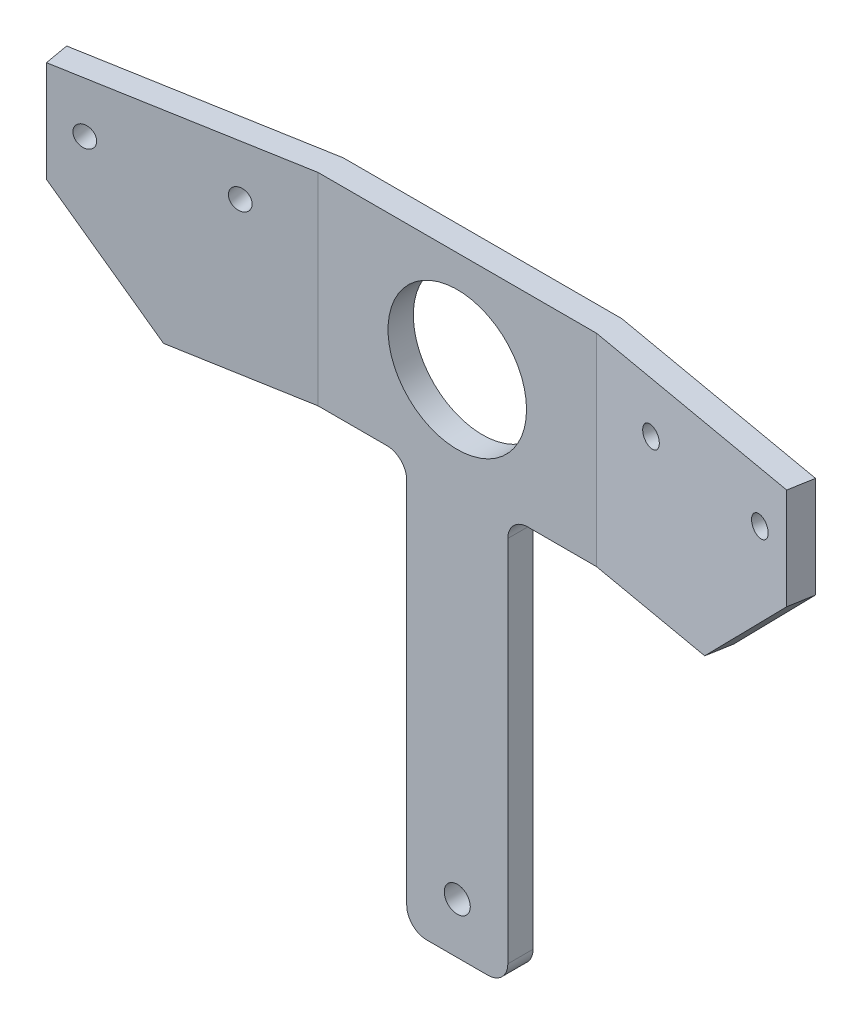
SolidWorks part; units mm, degrees
material "6061-T6 (SS)"
ref_plane "Front Plane" through (0, 0, 0) normal (0, 0, 1) x (1, 0, 0)
ref_plane "Top Plane" through (0, 0, 0) normal (0, 1, 0) x (1, 0, 0)
ref_plane "Right Plane" through (0, 0, 0) normal (1, 0, 0) x (0, 0, -1)
sketch "Sketch1" plane through (0, 0, 0) normal (0, 0, 1) x (1, 0, 0)
  line L0 (0, 0) -> (0, 12.7) construction
  line L1 (-12.7, 0) -> (12.7, 0)
  line L2 (-12.7, 0) -> (-12.7, 102.57)
  line L4 (12.7, 0) -> (12.7, 102.57)
  line L5 (0, 12.7) -> (0, 127.97) construction
  line L6 (-12.7, 102.57) -> (-35, 102.57)
  line L10 (35, 102.57) -> (12.7, 102.57)
  line L13 (-35, 153.37) -> (35, 153.37)
  line L16 (-90, 127.97) -> (90, 127.97) construction
  line L21 (-35, 153.37) -> (-97.3355, 153.37) construction
  line L22 (35, 153.37) -> (97.0498, 153.37) construction
  line L23 (-35, 153.37) -> (-35, 102.57)
  line L24 (35, 153.37) -> (35, 102.57)
  circle A0 centre (0, 127.97) radius 17.4
  circle A1 centre (0, 12.7) radius 3.265
  point P4 (0, 0)
  dimension "D4" = 34.8
  dimension "D5" = 6.53
  dimension "D1" = 25.4
  dimension "D2" = 12.7
  dimension "D3" = 115.27
  dimension "D6" = 25.4
  dimension "D7" = 35
  dimension "D12" = 70
  dimension "D16" = 25.4
extrude "Boss-Extrude1" add sketch "Sketch1" along normal blind 6.35
fillet "Fillet2" radius 5 4 edges at (-12.7, 0, 3.175) (12.7, 0, 3.175) (12.7, 102.57, 3.175) (-12.7, 102.57, 3.175)
sketch "Sketch2" plane through (0, 153.37, 0) normal (0, 1, 0) x (1, 0, 0)
  line L0 (-35, 0) -> (-94.0885, -10.4189)
  line L2 (-35, 0) -> (-94.2448, 0) construction
  line L4 (-93.0026, -16.5774) -> (-35, -6.35)
  line L5 (-94.0885, -10.4189) -> (-93.0026, -16.5774)
  line L9 (35, 0) -> (-35, 0)
  line L10 (-35, 0) -> (-35, -6.35)
  line L11 (-35, -6.35) -> (35, -6.35)
  line L12 (35, -6.35) -> (35, 0)
  line L14 (-35, 0) -> (-35, -6.35)
  dimension "D1" = 10
  dimension "D2" = 60
  dimension "D3" = 0
extrude "Boss-Extrude2" add sketch "Sketch2" against normal up to surface (50.8 mm away) up to face at (-26.35, 102.57, 3.175)
sketch "Sketch6" plane through (0.0305, 0, 0.1732) normal (0.1736, 0, 0.9848) x (0.9848, 0, -0.1736)
  line L1 (-94.4683, 102.57) -> (-94.4683, 153.37) construction
  line L5 (-94.4683, 102.57) -> (-94.4683, 127.97)
  line L6 (-94.4683, 127.97) -> (-69.0683, 102.57)
  line L7 (-94.4683, 102.57) -> (-35.5709, 102.57) construction
  line L8 (-69.0683, 102.57) -> (-94.4683, 102.57)
  line L9 (-1.1027, 0) -> (-1.1027, 173.3343) construction
  line L10 (-8.6857, 0) -> (6.4804, 0) construction
  dimension "D2" = 45
  dimension "D3" = 25.4
extrude "Cut-Extrude4" cut sketch "Sketch6" against normal through all both and the other way through all
mirror "Mirror1" about plane through (0, 0, 0) normal (1, 0, 0) of "Boss-Extrude2", "Cut-Extrude4"
sketch "Sketch8" plane through (1.0554, 0, -5.9854) normal (0.1736, 0, -0.9848) x (-0.9848, 0, -0.1736)
  circle A2 centre (-86.1622, 140.67) radius 2.575
  circle A3 centre (-52.4347, 140.67) radius 2.575
extrude "Cut-Extrude6" cut sketch "Sketch8" against normal blind 10
mirror "Mirror2" about plane through (0, 0, 0) normal (1, 0, 0) of "Cut-Extrude6"
